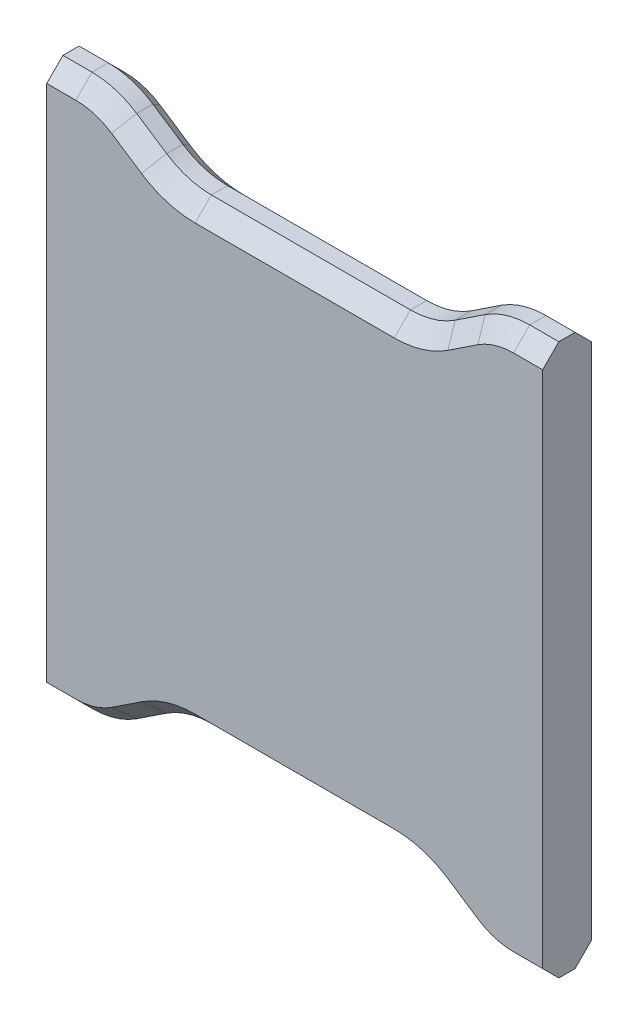
SolidWorks part; units mm, degrees
ref_plane "Alzado" through (0, 0, 0) normal (0, 0, 1) x (1, 0, 0)
ref_plane "Planta" through (0, 0, 0) normal (0, 1, 0) x (1, 0, 0)
ref_plane "Vista lateral" through (0, 0, 0) normal (1, 0, 0) x (0, 0, -1)
sketch "Croquis1" plane through (0, 0, 0) normal (0, 0, 1) x (1, 0, 0)
  line L1 (30.6, -34) -> (-30.6, -34)
  line L2 (30.6, -34) -> (30.6, 34)
  line L3 (30.6, 34) -> (-30.6, 34)
  line L4 (-30.6, -34) -> (-30.6, 34)
  line L5 (30.6, -34) -> (-30.6, 34) construction
  line L6 (30.6, 34) -> (-30.6, -34) construction
  point P0 (0, 0)
  dimension "D1" = 68
  dimension "D2" = 61.2
extrude "Saliente-Extruir1" add sketch "Croquis1" along normal blind 6
sketch "Croquis2" plane through (0, 0, 6) normal (0, 0, 1) x (1, 0, 0)
  line L0 (-41.4714, 0) -> (43.6912, 0) construction
  line L1 (0, 42.8525) -> (0, -17.3278) construction
  line L2 (-24, 34) -> (-15.2923, 28.2406)
  line L3 (30.6, 34) -> (-30.6, 34) construction
  line L4 (-15.2923, 28.2406) -> (15.2923, 28.2406)
  line L5 (-24, 34) -> (24, 34)
  line L6 (24, 34) -> (15.2923, 28.2406)
  line L7 (24, -34) -> (15.2923, -28.2406)
  line L8 (-24, -34) -> (24, -34)
  line L9 (-15.2923, -28.2406) -> (15.2923, -28.2406)
  line L10 (-24, -34) -> (-15.2923, -28.2406)
  point P10 (-15.5674, 26.4737)
  point P12 (0, 34)
  point P13 (0, 28.2406)
  point P14 (0, -28.2406)
  point P15 (0, -34)
  point P20 (-14.2173, 27.3537)
  point P21 (-22.8607, 34)
  point P22 (-13.2923, 28.2406)
  dimension "D1" = 48
extrude "Cortar-Extruir1" cut sketch "Croquis2" against normal through all
fillet "Redondeo1" radius 10 8 edges at (24, -34, 3) (15.2923, -28.2406, 3) (-24, -34, 3) (-15.2923, -28.2406, 3) (24, 34, 3) (15.2923, 28.2406, 3) (-24, 34, 3) (-15.2923, 28.2406, 3)
chamfer "Chaflán1" distance 2 angle 45 36 edges at (28.8039, -34, 0) (-28.8039, -34, 0) (24.1275, -33.5762, 0) (-24.1275, -33.5762, 0) (19.6461, -31.1203, 0) (-19.6461, -31.1203, 0) (15.1648, -28.6644, 0) (-15.1648, -28.6644, 0) (0, -28.2406, 0) (-28.8039, 34, 0) (28.8039, 34, 0) (-24.1275, 33.5762, 0) (24.1275, 33.5762, 0) (-19.6461, 31.1203, 0) (19.6461, 31.1203, 0) (-15.1648, 28.6644, 0) (15.1648, 28.6644, 0) (0, 28.2406, 0) (28.8039, -34, 6) (-28.8039, -34, 6) (24.1275, -33.5762, 6) (-24.1275, -33.5762, 6) (19.6461, -31.1203, 6) (-19.6461, -31.1203, 6) (15.1648, -28.6644, 6) (-15.1648, -28.6644, 6) (0, -28.2406, 6) (-28.8039, 34, 6) (28.8039, 34, 6) (-24.1275, 33.5762, 6) (24.1275, 33.5762, 6) (-19.6461, 31.1203, 6) (19.6461, 31.1203, 6) (-15.1648, 28.6644, 6) (15.1648, 28.6644, 6) (0, 28.2406, 6)
